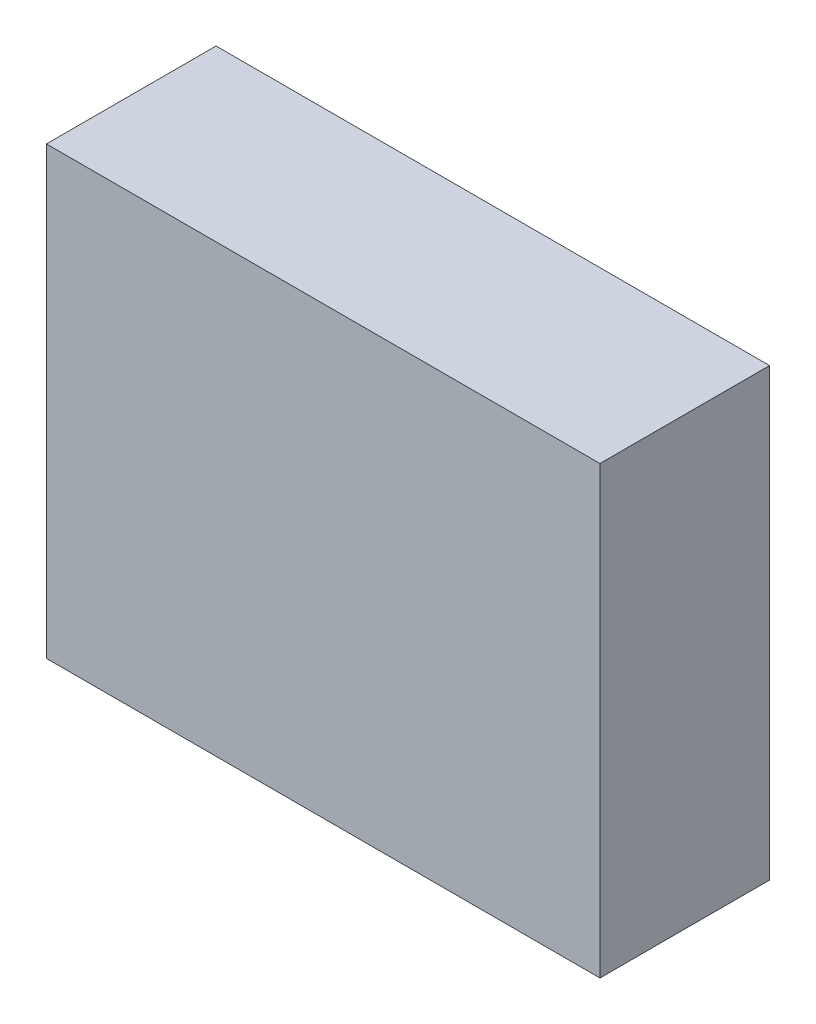
SolidWorks part; units mm, degrees
ref_plane "Plan de face" through (0, 0, 0) normal (0, 0, 1) x (1, 0, 0)
ref_plane "Plan de dessus" through (0, 0, 0) normal (0, 1, 0) x (1, 0, 0)
ref_plane "Plan de droite" through (0, 0, 0) normal (1, 0, 0) x (0, 0, -1)
sketch "Esquisse1" plane through (0, 0, 0) normal (0, 0, 1) x (1, 0, 0)
  line L0 (-1.6635, 1.3135) -> (1.6, 1.3135)
  line L1 (1.6, 1.3135) -> (1.6, -1.3135)
  line L2 (1.6, -1.3135) -> (-1.6635, -1.3135)
  line L3 (-1.6635, -1.3135) -> (-1.6635, 1.3135)
extrude "Component_Outline" add sketch "Esquisse1" along normal blind 1 separate body
sketch3d "Esquisse3D1"
  line L0 (0, 0, 0) -> (1, 0, 0)
  line L1 (0, 0, 0) -> (0, 1, 0)
  line L2 (0, 0, 0) -> (0, 0, 1)
  point P0 (0, 0, 0)
